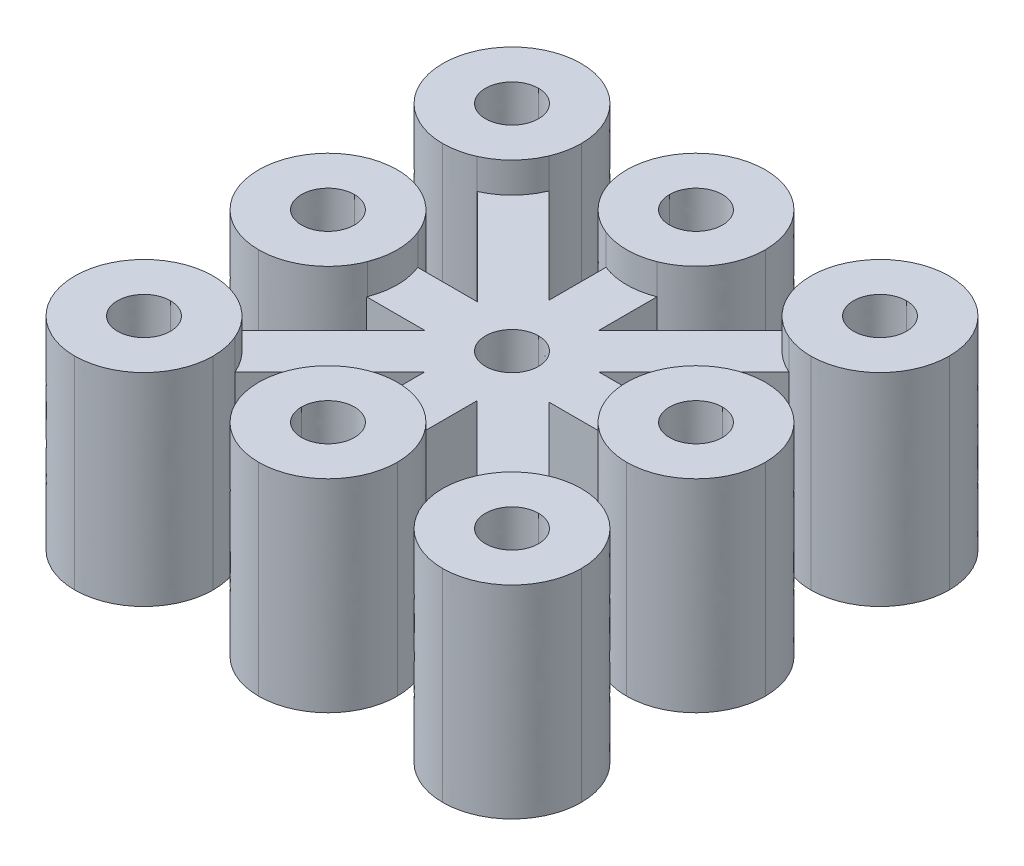
SolidWorks part; units mm, degrees
ref_plane "Front Plane" through (0, 0, 0) normal (0, 0, 1) x (1, 0, 0)
ref_plane "Top Plane" through (0, 0, 0) normal (0, 1, 0) x (1, 0, 0)
ref_plane "Right Plane" through (0, 0, 0) normal (1, 0, 0) x (0, 0, -1)
sketch "Model" plane through (0, 0, 0) normal (0, 1, 0) x (1, 0, 0)
  line L0 (11.801, 27.5033) -> (6.0457, 27.5033)
  line L1 (6.0457, 27.5033) -> (15.4347, 36.8902)
  line L2 (11.8902, 40.4389) -> (2.5158, 31.0623)
  line L3 (2.5158, 31.0623) -> (2.5158, 36.8011)
  line L4 (-2.522, 36.8052) -> (-2.522, 31.1556)
  line L5 (-2.522, 31.1556) -> (-11.8612, 40.499)
  line L6 (-15.3538, 36.9255) -> (-5.9254, 27.5033)
  line L7 (-5.9254, 27.5033) -> (-11.7969, 27.5033)
  line L8 (-11.8073, 22.4656) -> (-6.081, 22.4656)
  line L9 (-6.081, 22.4656) -> (-15.4368, 13.1118)
  line L10 (-11.8902, 9.5653) -> (-2.522, 18.9377)
  line L11 (-2.522, 18.9377) -> (-2.522, 13.1948)
  line L12 (2.5158, 13.1989) -> (2.5158, 19.0538)
  line L13 (2.5158, 19.0538) -> (11.9255, 9.642)
  line L14 (15.5031, 13.1388) -> (6.1784, 22.4656)
  line L15 (6.1784, 22.4656) -> (11.8114, 22.4656)
  spline S0 degree 3 poles (18.1641, 18.162) (21.9408, 18.162) (25.0021, 21.2232) (25.0021, 25) knots 0 0 0 0 1 1 1 1
  spline S1 degree 3 poles (25.0021, 25) (25.0021, 28.7768) (21.9408, 31.838) (18.1641, 31.838) knots 1 1 1 1 2 2 2 2
  spline S2 degree 3 poles (18.1641, 31.838) (15.2729, 31.838) (12.7986, 30.0419) (11.801, 27.5033) knots 2 2 2 2 3 3 3 3
  spline S3 degree 3 poles (15.4347, 36.8902) (16.2705, 36.5273) (17.1934, 36.324) (18.1641, 36.324) knots 5 5 5 5 6 6 6 6
  spline S4 degree 3 poles (18.1641, 36.324) (21.9408, 36.3246) (25.0016, 39.3863) (25.001, 43.1631) knots 6 6 6 6 7 7 7 7
  spline S5 degree 3 poles (25.001, 43.1631) (25.0005, 46.9398) (21.9388, 50.0006) (18.162, 50) knots 7 7 7 7 8 8 8 8
  spline S6 degree 3 poles (18.162, 50) (14.3873, 50) (11.3261, 46.9388) (11.3261, 43.162) knots 8 8 8 8 9 9 9 9
  spline S7 degree 3 poles (11.3261, 43.162) (11.3261, 42.1935) (11.5273, 41.2726) (11.8902, 40.4389) knots 9 9 9 9 10 10 10 10
  spline S8 degree 3 poles (2.5158, 36.8011) (5.0481, 37.8028) (6.838, 40.2729) (6.838, 43.162) knots 12 12 12 12 13 13 13 13
  spline S9 degree 3 poles (6.838, 43.162) (6.838, 46.9388) (3.7767, 50) (0, 50) knots 13 13 13 13 14 14 14 14
  spline S10 degree 3 poles (0, 50) (-3.7747, 50) (-6.8359, 46.9388) (-6.8359, 43.162) knots 14 14 14 14 15 15 15 15
  spline S11 degree 3 poles (-6.8359, 43.162) (-6.8359, 40.2771) (-5.0502, 37.809) (-2.522, 36.8052) knots 15 15 15 15 16 16 16 16
  spline S12 degree 3 poles (-11.8612, 40.499) (-11.5149, 41.3182) (-11.3241, 42.2184) (-11.3241, 43.162) knots 18 18 18 18 19 19 19 19
  spline S13 degree 3 poles (-11.3241, 43.162) (-11.3241, 46.9388) (-14.3853, 50) (-18.1599, 50) knots 19 19 19 19 20 20 20 20
  spline S14 degree 3 poles (-18.1599, 50) (-21.9367, 50) (-24.9979, 46.9388) (-24.9979, 43.162) knots 20 20 20 20 21 21 21 21
  spline S15 degree 3 poles (-24.9979, 43.162) (-24.9979, 39.3853) (-21.9367, 36.324) (-18.1599, 36.324) knots 21 21 21 21 22 22 22 22
  spline S16 degree 3 poles (-18.1599, 36.324) (-17.1603, 36.324) (-16.2104, 36.5397) (-15.3538, 36.9255) knots 22 22 22 22 23 23 23 23
  spline S17 degree 3 poles (-11.7969, 27.5033) (-12.7945, 30.0419) (-15.2688, 31.838) (-18.1599, 31.838) knots 25 25 25 25 26 26 26 26
  spline S18 degree 3 poles (-18.1599, 31.838) (-21.9367, 31.838) (-24.9979, 28.7768) (-24.9979, 25) knots 26 26 26 26 27 27 27 27
  spline S19 degree 3 poles (-24.9979, 25) (-24.9979, 21.2232) (-21.9367, 18.162) (-18.1599, 18.162) knots 27 27 27 27 28 28 28 28
  spline S20 degree 3 poles (-18.1599, 18.162) (-15.2543, 18.162) (-12.7738, 19.9747) (-11.7824, 22.5319) knots 28 28 28 28 29 29 29 29
  spline S21 degree 3 poles (-11.7824, 22.5319) (-11.7907, 22.5091) (-11.799, 22.4884) (-11.8073, 22.4656) knots 29 29 29 29 30 30 30 30
  spline S22 degree 3 poles (-15.4368, 13.1118) (-16.2705, 13.4748) (-17.1914, 13.676) (-18.1599, 13.676) knots 32 32 32 32 33 33 33 33
  spline S23 degree 3 poles (-18.1599, 13.676) (-21.9367, 13.676) (-24.9979, 10.6147) (-24.9979, 6.838) knots 33 33 33 33 34 34 34 34
  spline S24 degree 3 poles (-24.9979, 6.838) (-24.9979, 3.0612) (-21.9367, 0) (-18.1599, 0) knots 34 34 34 34 35 35 35 35
  spline S25 degree 3 poles (-18.1599, 0) (-14.3853, 0) (-11.3241, 3.0612) (-11.3241, 6.838) knots 35 35 35 35 36 36 36 36
  spline S26 degree 3 poles (-11.3241, 6.838) (-11.3241, 7.8065) (-11.5252, 8.7295) (-11.8902, 9.5653) knots 36 36 36 36 37 37 37 37
  spline S27 degree 3 poles (-2.522, 13.1948) (-5.0502, 12.191) (-6.8359, 9.7229) (-6.8359, 6.838) knots 39 39 39 39 40 40 40 40
  spline S28 degree 3 poles (-6.8359, 6.838) (-6.8359, 3.0612) (-3.7747, 0) (0, 0) knots 40 40 40 40 41 41 41 41
  spline S29 degree 3 poles (0, 0) (3.7767, 0) (6.838, 3.0612) (6.838, 6.838) knots 41 41 41 41 42 42 42 42
  spline S30 degree 3 poles (6.838, 6.838) (6.838, 9.7271) (5.0481, 12.1972) (2.5158, 13.1989) knots 42 42 42 42 43 43 43 43
  spline S31 degree 3 poles (11.9255, 9.642) (11.5397, 8.7855) (11.3261, 7.8376) (11.3261, 6.838) knots 45 45 45 45 46 46 46 46
  spline S32 degree 3 poles (11.3261, 6.838) (11.3261, 3.0612) (14.3873, 0) (18.162, 0) knots 46 46 46 46 47 47 47 47
  spline S33 degree 3 poles (18.162, 0) (21.9388, -0.0006) (25.0005, 3.0602) (25.001, 6.8369) knots 47 47 47 47 48 48 48 48
  spline S34 degree 3 poles (25.001, 6.8369) (25.0016, 10.6137) (21.9408, 13.6754) (18.1641, 13.676) knots 48 48 48 48 49 49 49 49
  spline S35 degree 3 poles (18.1641, 13.676) (17.2204, 13.676) (16.3203, 13.4851) (15.5031, 13.1388) knots 49 49 49 49 50 50 50 50
  spline S36 degree 3 poles (11.8114, 22.4656) (11.8031, 22.4884) (11.7948, 22.5091) (11.7865, 22.5319) knots 52 52 52 52 53 53 53 53
  spline S37 degree 3 poles (11.7865, 22.5319) (12.7779, 19.9747) (15.2584, 18.162) (18.1641, 18.162) knots 53 53 53 53 54 54 54 54
  spline S38 degree 3 poles (18.162, 22.3847) (16.7206, 22.3847) (15.5488, 23.5586) (15.5488, 25) (15.5488, 26.4414) (16.7206, 27.6132) (18.162, 27.6132) knots 2 2 2 2 3 3 3 4 4 4 4
  spline S39 degree 3 poles (18.162, 27.6132) (19.6034, 27.6132) (20.7773, 26.4414) (20.7773, 25) (20.7773, 23.5586) (19.6034, 22.3847) (18.162, 22.3847) knots 0 0 0 0 1 1 1 2 2 2 2
  spline S40 degree 3 poles (18.162, 40.5467) (16.7206, 40.5467) (15.5488, 41.7206) (15.5488, 43.162) (15.5488, 44.6035) (16.7206, 45.7753) (18.162, 45.7753) knots 2 2 2 2 3 3 3 4 4 4 4
  spline S41 degree 3 poles (18.162, 45.7753) (19.6034, 45.7753) (20.7773, 44.6035) (20.7773, 43.162) (20.7773, 41.7206) (19.6034, 40.5467) (18.162, 40.5467) knots 0 0 0 0 1 1 1 2 2 2 2
  spline S42 degree 3 poles (-18.1599, 45.7753) (-16.7185, 45.7753) (-15.5467, 44.6035) (-15.5467, 43.162) (-15.5467, 41.7206) (-16.7185, 40.5467) (-18.1599, 40.5467) knots 2 2 2 2 3 3 3 4 4 4 4
  spline S43 degree 3 poles (-18.1599, 40.5467) (-19.6014, 40.5467) (-20.7753, 41.7206) (-20.7753, 43.162) (-20.7753, 44.6035) (-19.6014, 45.7753) (-18.1599, 45.7753) knots 0 0 0 0 1 1 1 2 2 2 2
  spline S44 degree 3 poles (-18.1599, 27.6132) (-16.7185, 27.6132) (-15.5467, 26.4414) (-15.5467, 25) (-15.5467, 23.5586) (-16.7185, 22.3847) (-18.1599, 22.3847) knots 2 2 2 2 3 3 3 4 4 4 4
  spline S45 degree 3 poles (-18.1599, 22.3847) (-19.6014, 22.3847) (-20.7753, 23.5586) (-20.7753, 25) (-20.7753, 26.4414) (-19.6014, 27.6132) (-18.1599, 27.6132) knots 0 0 0 0 1 1 1 2 2 2 2
  spline S46 degree 3 poles (-18.1599, 9.4533) (-16.7185, 9.4533) (-15.5467, 8.2794) (-15.5467, 6.838) (-15.5467, 5.3965) (-16.7185, 4.2247) (-18.1599, 4.2247) knots 2 2 2 2 3 3 3 4 4 4 4
  spline S47 degree 3 poles (-18.1599, 4.2247) (-19.6014, 4.2247) (-20.7753, 5.3965) (-20.7753, 6.838) (-20.7753, 8.2794) (-19.6014, 9.4533) (-18.1599, 9.4533) knots 0 0 0 0 1 1 1 2 2 2 2
  spline S48 degree 3 poles (2.6153, 43.162) (2.6153, 41.7206) (1.4435, 40.5467) (0, 40.5467) (-1.4414, 40.5467) (-2.6132, 41.7206) (-2.6132, 43.162) knots 2 2 2 2 3 3 3 4 4 4 4
  spline S49 degree 3 poles (-2.6132, 43.162) (-2.6132, 44.6035) (-1.4414, 45.7753) (0, 45.7753) (1.4435, 45.7753) (2.6153, 44.6035) (2.6153, 43.162) knots 0 0 0 0 1 1 1 2 2 2 2
  spline S50 degree 3 poles (-2.6132, 6.838) (-2.6132, 8.2794) (-1.4414, 9.4533) (0, 9.4533) (1.4435, 9.4533) (2.6153, 8.2794) (2.6153, 6.838) knots 2 2 2 2 3 3 3 4 4 4 4
  spline S51 degree 3 poles (2.6153, 6.838) (2.6153, 5.3965) (1.4435, 4.2247) (0, 4.2247) (-1.4414, 4.2247) (-2.6132, 5.3965) (-2.6132, 6.838) knots 0 0 0 0 1 1 1 2 2 2 2
  spline S52 degree 3 poles (0, 27.6153) (1.4456, 27.6153) (2.6153, 26.4435) (2.6153, 25) (2.6153, 23.5565) (1.4456, 22.3847) (0, 22.3847) knots 2 2 2 2 3 3 3 4 4 4 4
  spline S53 degree 3 poles (0, 22.3847) (-1.4435, 22.3847) (-2.6132, 23.5565) (-2.6132, 25) (-2.6132, 26.4435) (-1.4435, 27.6153) (0, 27.6153) knots 0 0 0 0 1 1 1 2 2 2 2
  spline S54 degree 3 poles (18.162, 4.2247) (16.7206, 4.2247) (15.5488, 5.3965) (15.5488, 6.838) (15.5488, 8.2794) (16.7206, 9.4533) (18.162, 9.4533) knots 2 2 2 2 3 3 3 4 4 4 4
  spline S55 degree 3 poles (18.162, 9.4533) (19.6034, 9.4533) (20.7773, 8.2794) (20.7773, 6.838) (20.7773, 5.3965) (19.6034, 4.2247) (18.162, 4.2247) knots 0 0 0 0 1 1 1 2 2 2 2
  spline S56 degree 3 poles (-18.1599, 22.3847) (-16.7185, 22.3847) (-15.5467, 23.5586) (-15.5467, 25) (-15.5467, 26.4414) (-16.7185, 27.6132) (-18.1599, 27.6132) knots 2 2 2 2 3 3 3 4 4 4 4
  spline S57 degree 3 poles (-18.1599, 27.6132) (-19.6014, 27.6132) (-20.7753, 26.4414) (-20.7753, 25) (-20.7753, 23.5586) (-19.6014, 22.3847) (-18.1599, 22.3847) knots 0 0 0 0 1 1 1 2 2 2 2
  spline S58 degree 3 poles (-18.1599, 22.3847) (-16.7185, 22.3847) (-15.5467, 23.5586) (-15.5467, 25) (-15.5467, 26.4414) (-16.7185, 27.6132) (-18.1599, 27.6132) knots 2 2 2 2 3 3 3 4 4 4 4
  spline S59 degree 3 poles (-18.1599, 27.6132) (-19.6014, 27.6132) (-20.7753, 26.4414) (-20.7753, 25) (-20.7753, 23.5586) (-19.6014, 22.3847) (-18.1599, 22.3847) knots 0 0 0 0 1 1 1 2 2 2 2
  spline S60 degree 3 poles (-18.1599, 22.3847) (-16.7185, 22.3847) (-15.5467, 23.5586) (-15.5467, 25) (-15.5467, 26.4414) (-16.7185, 27.6132) (-18.1599, 27.6132) knots 2 2 2 2 3 3 3 4 4 4 4
  spline S61 degree 3 poles (-18.1599, 27.6132) (-19.6014, 27.6132) (-20.7753, 26.4414) (-20.7753, 25) (-20.7753, 23.5586) (-19.6014, 22.3847) (-18.1599, 22.3847) knots 0 0 0 0 1 1 1 2 2 2 2
  spline S62 degree 3 poles (18.162, 22.3847) (19.6034, 22.3847) (20.7773, 23.5586) (20.7773, 25) (20.7773, 26.4414) (19.6034, 27.6132) (18.162, 27.6132) knots 2 2 2 2 3 3 3 4 4 4 4
  spline S63 degree 3 poles (18.162, 27.6132) (16.7206, 27.6132) (15.5488, 26.4414) (15.5488, 25) (15.5488, 23.5586) (16.7206, 22.3847) (18.162, 22.3847) knots 0 0 0 0 1 1 1 2 2 2 2
  spline S64 degree 3 poles (18.162, 22.3847) (19.6034, 22.3847) (20.7773, 23.5586) (20.7773, 25) (20.7773, 26.4414) (19.6034, 27.6132) (18.162, 27.6132) knots 2 2 2 2 3 3 3 4 4 4 4
  spline S65 degree 3 poles (18.162, 27.6132) (16.7206, 27.6132) (15.5488, 26.4414) (15.5488, 25) (15.5488, 23.5586) (16.7206, 22.3847) (18.162, 22.3847) knots 0 0 0 0 1 1 1 2 2 2 2
  spline S66 degree 3 poles (18.162, 22.3847) (19.6034, 22.3847) (20.7773, 23.5586) (20.7773, 25) (20.7773, 26.4414) (19.6034, 27.6132) (18.162, 27.6132) knots 2 2 2 2 3 3 3 4 4 4 4
  spline S67 degree 3 poles (18.162, 27.6132) (16.7206, 27.6132) (15.5488, 26.4414) (15.5488, 25) (15.5488, 23.5586) (16.7206, 22.3847) (18.162, 22.3847) knots 0 0 0 0 1 1 1 2 2 2 2
  spline S68 degree 3 poles (-18.1599, 4.2247) (-16.7185, 4.2247) (-15.5467, 5.3965) (-15.5467, 6.838) (-15.5467, 8.2794) (-16.7185, 9.4533) (-18.1599, 9.4533) knots 2 2 2 2 3 3 3 4 4 4 4
  spline S69 degree 3 poles (-18.1599, 9.4533) (-19.6014, 9.4533) (-20.7753, 8.2794) (-20.7753, 6.838) (-20.7753, 5.3965) (-19.6014, 4.2247) (-18.1599, 4.2247) knots 0 0 0 0 1 1 1 2 2 2 2
  spline S70 degree 3 poles (-18.1599, 4.2247) (-16.7185, 4.2247) (-15.5467, 5.3965) (-15.5467, 6.838) (-15.5467, 8.2794) (-16.7185, 9.4533) (-18.1599, 9.4533) knots 2 2 2 2 3 3 3 4 4 4 4
  spline S71 degree 3 poles (-18.1599, 9.4533) (-19.6014, 9.4533) (-20.7753, 8.2794) (-20.7753, 6.838) (-20.7753, 5.3965) (-19.6014, 4.2247) (-18.1599, 4.2247) knots 0 0 0 0 1 1 1 2 2 2 2
  spline S72 degree 3 poles (-18.1599, 4.2247) (-16.7185, 4.2247) (-15.5467, 5.3965) (-15.5467, 6.838) (-15.5467, 8.2794) (-16.7185, 9.4533) (-18.1599, 9.4533) knots 2 2 2 2 3 3 3 4 4 4 4
  spline S73 degree 3 poles (-18.1599, 9.4533) (-19.6014, 9.4533) (-20.7753, 8.2794) (-20.7753, 6.838) (-20.7753, 5.3965) (-19.6014, 4.2247) (-18.1599, 4.2247) knots 0 0 0 0 1 1 1 2 2 2 2
  spline S74 degree 3 poles (0, 4.2247) (1.4435, 4.2247) (2.6153, 5.3965) (2.6153, 6.838) (2.6153, 8.2794) (1.4435, 9.4533) (0, 9.4533) knots 2 2 2 2 3 3 3 4 4 4 4
  spline S75 degree 3 poles (0, 9.4533) (-1.4414, 9.4533) (-2.6132, 8.2794) (-2.6132, 6.838) (-2.6132, 5.3965) (-1.4414, 4.2247) (0, 4.2247) knots 0 0 0 0 1 1 1 2 2 2 2
  spline S76 degree 3 poles (0, 4.2247) (1.4435, 4.2247) (2.6153, 5.3965) (2.6153, 6.838) (2.6153, 8.2794) (1.4435, 9.4533) (0, 9.4533) knots 2 2 2 2 3 3 3 4 4 4 4
  spline S77 degree 3 poles (0, 9.4533) (-1.4414, 9.4533) (-2.6132, 8.2794) (-2.6132, 6.838) (-2.6132, 5.3965) (-1.4414, 4.2247) (0, 4.2247) knots 0 0 0 0 1 1 1 2 2 2 2
  spline S78 degree 3 poles (0, 4.2247) (1.4435, 4.2247) (2.6153, 5.3965) (2.6153, 6.838) (2.6153, 8.2794) (1.4435, 9.4533) (0, 9.4533) knots 2 2 2 2 3 3 3 4 4 4 4
  spline S79 degree 3 poles (0, 9.4533) (-1.4414, 9.4533) (-2.6132, 8.2794) (-2.6132, 6.838) (-2.6132, 5.3965) (-1.4414, 4.2247) (0, 4.2247) knots 0 0 0 0 1 1 1 2 2 2 2
  spline S80 degree 3 poles (18.162, 4.2247) (19.6034, 4.2247) (20.7773, 5.3965) (20.7773, 6.838) (20.7773, 8.2794) (19.6034, 9.4533) (18.162, 9.4533) knots 2 2 2 2 3 3 3 4 4 4 4
  spline S81 degree 3 poles (18.162, 9.4533) (16.7206, 9.4533) (15.5488, 8.2794) (15.5488, 6.838) (15.5488, 5.3965) (16.7206, 4.2247) (18.162, 4.2247) knots 0 0 0 0 1 1 1 2 2 2 2
  spline S82 degree 3 poles (18.162, 4.2247) (19.6034, 4.2247) (20.7773, 5.3965) (20.7773, 6.838) (20.7773, 8.2794) (19.6034, 9.4533) (18.162, 9.4533) knots 2 2 2 2 3 3 3 4 4 4 4
  spline S83 degree 3 poles (18.162, 9.4533) (16.7206, 9.4533) (15.5488, 8.2794) (15.5488, 6.838) (15.5488, 5.3965) (16.7206, 4.2247) (18.162, 4.2247) knots 0 0 0 0 1 1 1 2 2 2 2
  spline S84 degree 3 poles (18.162, 4.2247) (19.6034, 4.2247) (20.7773, 5.3965) (20.7773, 6.838) (20.7773, 8.2794) (19.6034, 9.4533) (18.162, 9.4533) knots 2 2 2 2 3 3 3 4 4 4 4
  spline S85 degree 3 poles (18.162, 9.4533) (16.7206, 9.4533) (15.5488, 8.2794) (15.5488, 6.838) (15.5488, 5.3965) (16.7206, 4.2247) (18.162, 4.2247) knots 0 0 0 0 1 1 1 2 2 2 2
  spline S86 degree 3 poles (0, 40.5467) (1.4435, 40.5467) (2.6153, 41.7206) (2.6153, 43.162) (2.6153, 44.6035) (1.4435, 45.7753) (0, 45.7753) knots 2 2 2 2 3 3 3 4 4 4 4
  spline S87 degree 3 poles (0, 45.7753) (-1.4414, 45.7753) (-2.6132, 44.6035) (-2.6132, 43.162) (-2.6132, 41.7206) (-1.4414, 40.5467) (0, 40.5467) knots 0 0 0 0 1 1 1 2 2 2 2
  spline S88 degree 3 poles (0, 40.5467) (1.4435, 40.5467) (2.6153, 41.7206) (2.6153, 43.162) (2.6153, 44.6035) (1.4435, 45.7753) (0, 45.7753) knots 2 2 2 2 3 3 3 4 4 4 4
  spline S89 degree 3 poles (0, 45.7753) (-1.4414, 45.7753) (-2.6132, 44.6035) (-2.6132, 43.162) (-2.6132, 41.7206) (-1.4414, 40.5467) (0, 40.5467) knots 0 0 0 0 1 1 1 2 2 2 2
  spline S90 degree 3 poles (0, 40.5467) (1.4435, 40.5467) (2.6153, 41.7206) (2.6153, 43.162) (2.6153, 44.6035) (1.4435, 45.7753) (0, 45.7753) knots 2 2 2 2 3 3 3 4 4 4 4
  spline S91 degree 3 poles (0, 45.7753) (-1.4414, 45.7753) (-2.6132, 44.6035) (-2.6132, 43.162) (-2.6132, 41.7206) (-1.4414, 40.5467) (0, 40.5467) knots 0 0 0 0 1 1 1 2 2 2 2
  spline S92 degree 3 poles (18.162, 40.5467) (19.6034, 40.5467) (20.7773, 41.7206) (20.7773, 43.162) (20.7773, 44.6035) (19.6034, 45.7753) (18.162, 45.7753) knots 2 2 2 2 3 3 3 4 4 4 4
  spline S93 degree 3 poles (18.162, 45.7753) (16.7206, 45.7753) (15.5488, 44.6035) (15.5488, 43.162) (15.5488, 41.7206) (16.7206, 40.5467) (18.162, 40.5467) knots 0 0 0 0 1 1 1 2 2 2 2
  spline S94 degree 3 poles (18.162, 40.5467) (19.6034, 40.5467) (20.7773, 41.7206) (20.7773, 43.162) (20.7773, 44.6035) (19.6034, 45.7753) (18.162, 45.7753) knots 2 2 2 2 3 3 3 4 4 4 4
  spline S95 degree 3 poles (18.162, 45.7753) (16.7206, 45.7753) (15.5488, 44.6035) (15.5488, 43.162) (15.5488, 41.7206) (16.7206, 40.5467) (18.162, 40.5467) knots 0 0 0 0 1 1 1 2 2 2 2
  spline S96 degree 3 poles (18.162, 40.5467) (19.6034, 40.5467) (20.7773, 41.7206) (20.7773, 43.162) (20.7773, 44.6035) (19.6034, 45.7753) (18.162, 45.7753) knots 2 2 2 2 3 3 3 4 4 4 4
  spline S97 degree 3 poles (18.162, 45.7753) (16.7206, 45.7753) (15.5488, 44.6035) (15.5488, 43.162) (15.5488, 41.7206) (16.7206, 40.5467) (18.162, 40.5467) knots 0 0 0 0 1 1 1 2 2 2 2
  dimension "D1" = 50
  dimension "D2" = 50
extrude "Boss-Extrude1" add sketch "Model" along normal blind 20 contours S36 S37 S0 S1 S2 L0 L1 S3 S4 S5 S6 S7 L2 L3 S8 S9 S10 S11 L4 L5 S12 S13 S14 S15 S16 L6 L7 S17 S18 S19 S20 S21 L8 L9 S22 S23 S24 S25 S26 L10 L11 S27 S28 S29 S30 L12 L13 S31 S32 S33 S34
sketch "Sketch3" plane through (0, 20, 0) normal (0, 1, 0) x (1, 0, 0)
  line L0 (11.8902, 40.4389) -> (2.5158, 31.0623)
  line L1 (2.5158, 31.0623) -> (2.5158, 36.8011)
  line L2 (-2.522, 36.8052) -> (-2.522, 31.1556)
  line L3 (-2.522, 31.1556) -> (-11.8612, 40.499)
  line L4 (-15.3538, 36.9255) -> (-5.9254, 27.5033)
  line L5 (-5.9254, 27.5033) -> (-11.7969, 27.5033)
  line L6 (-11.8073, 22.4656) -> (-6.081, 22.4656)
  line L7 (-6.081, 22.4656) -> (-15.4368, 13.1118)
  line L8 (-11.8902, 9.5653) -> (-2.522, 18.9377)
  line L9 (-2.522, 18.9377) -> (-2.522, 13.1948)
  line L10 (2.5158, 13.1989) -> (2.5158, 19.0538)
  line L11 (2.5158, 19.0538) -> (11.9255, 9.642)
  line L12 (15.5031, 13.1388) -> (6.1784, 22.4656)
  line L13 (6.1784, 22.4656) -> (11.8114, 22.4656)
  line L14 (11.801, 27.5033) -> (6.0457, 27.5033)
  line L15 (6.0457, 27.5033) -> (15.4347, 36.8902)
  line L18 (0, 27.6153) -> (0, 22.3847) construction
  line L19 (-11.808, 22.4666) -> (-11.8073, 22.4656)
  line L20 (11.8114, 22.4705) -> (11.8114, 22.4656)
  arc A0 (-15.3536, 36.9252) -> (-11.8612, 40.499) centre (-18.1599, 43.161) ccw
  arc A1 (-2.522, 36.8044) -> (2.5158, 36.8011) centre (0.001, 43.162) ccw
  arc A2 (11.8894, 40.438) -> (15.4347, 36.8902) centre (18.162, 43.161) ccw
  arc A3 (-11.808, 22.4666) -> (-11.7969, 27.5033) centre (-18.1599, 24.999) ccw
  arc A4 (15.5031, 13.1388) -> (11.9252, 9.6423) centre (18.162, 6.839) ccw
  arc A5 (2.5158, 13.1989) -> (-2.522, 13.1965) centre (0, 6.839) ccw
  circle A6 centre (0, 25) radius 2.5694
  arc A7 (11.801, 27.5033) -> (11.8114, 22.4705) centre (18.162, 25) ccw
  arc A8 (-11.889, 9.5665) -> (-15.4368, 13.1118) centre (-18.1599, 6.839) ccw
extrude "Cut-Extrude1" cut sketch "Sketch3" against normal blind 3
ref_plane "Plane1" through (0, 10, 0) normal (0, 1, 0) x (1, 0, 0)
mirror "Mirror2" about plane through (0, 10, 0) normal (0, 1, 0) of "Cut-Extrude1"
